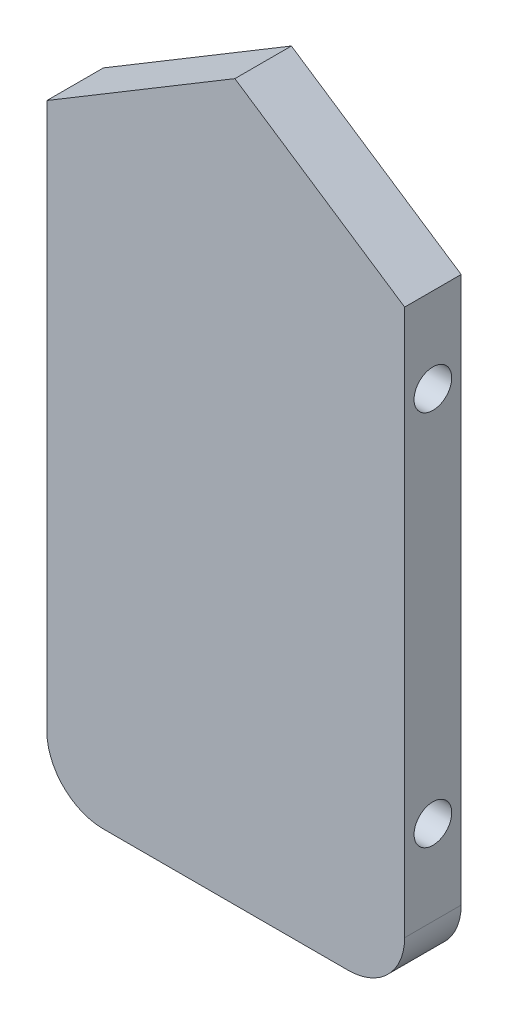
SolidWorks part; units mm, degrees
material "ABS"
ref_plane "Front Plane" through (0, 0, 0) normal (0, 0, 1) x (1, 0, 0)
ref_plane "Top Plane" through (0, 0, 0) normal (0, 1, 0) x (1, 0, 0)
ref_plane "Right Plane" through (0, 0, 0) normal (1, 0, 0) x (0, 0, -1)
sketch "Sketch3" plane through (0, 0, 0) normal (0, 0, 1) x (1, 0, 0)
  line L0 (0, 0) -> (152.4, 0)
  line L1 (0, 0) -> (-355.6, 0)
  line L2 (-228.6, -406.4) -> (-228.6, 330.2)
  line L5 (-152.4, -482.6) -> (177.8, -482.6)
  line L6 (-228.6, 482.6) -> (254, -482.6) construction
  line L7 (-228.6, -482.6) -> (254, 482.6) construction
  line L8 (-228.6, 330.2) -> (25.0362, 482.6)
  line L9 (0, 0) -> (25.0362, 482.6) construction
  line L11 (254, 330.2) -> (25.0362, 482.6)
  line L12 (254, 330.2) -> (254, -406.4)
  arc A0 (177.8, -482.6) -> (254, -406.4) centre (177.8, -406.4) ccw
  arc A1 (-152.4, -482.6) -> (-228.6, -406.4) centre (-152.4, -406.4) cw
  dimension "D7" = 76.2
  dimension "D1" = 965.2
  dimension "D2" = 508
  dimension "D3" = 152.4
  dimension "D4" = 152.4
  dimension "D5" = 59
  dimension "D6" = 152.4
  dimension "D8" = 152.4
extrude "Boss-Extrude1" add sketch "Sketch3" along normal mid plane 76.2 contours L12 L11 L8 L2 L1 L0 | A1 L5 A0 L12 L0 L1 L2
sketch "Sketch4" plane through (-228.6, 0, 0) normal (-1, 0, 0) x (0, 0, 1)
  line L0 (0, 330.2) -> (0, -406.4) construction
  line L1 (38.1, 330.2) -> (-38.1, 330.2) construction
  line L2 (38.1, -406.4) -> (-38.1, -406.4) construction
  circle A0 centre (0, 215.9) radius 25.4
  circle A1 centre (0, -292.1) radius 25.4
  dimension "D1" = 292.1
  dimension "D2" = 508
extrude "Cut-Extrude1" cut sketch "Sketch4" against normal through all
